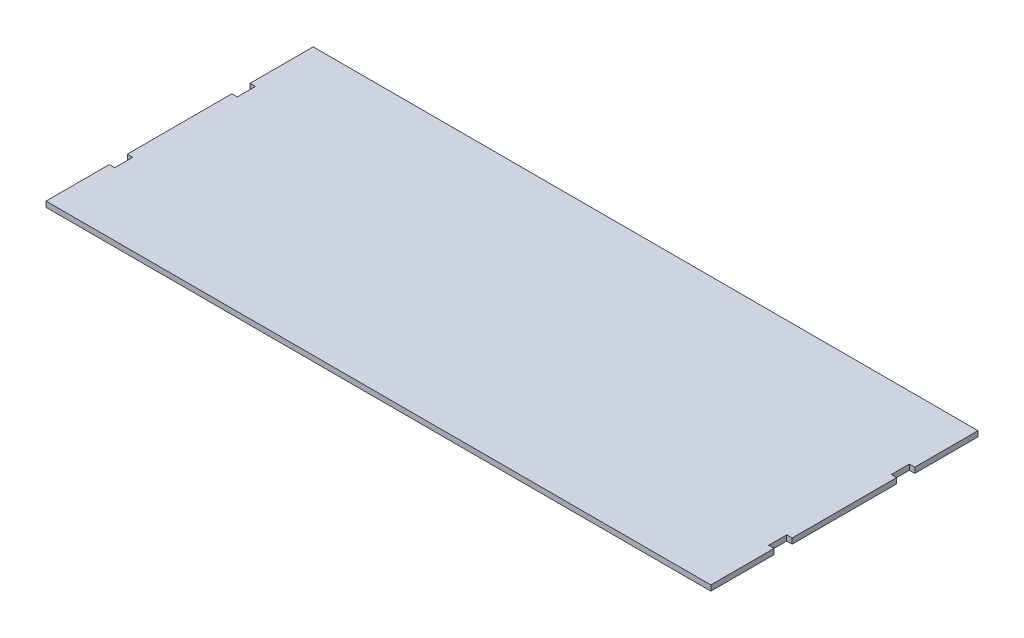
SolidWorks part; units mm, degrees
ref_plane "Front Plane" through (0, 0, 0) normal (0, 0, 1) x (1, 0, 0)
ref_plane "Top Plane" through (0, 0, 0) normal (0, 1, 0) x (1, 0, 0)
ref_plane "Right Plane" through (0, 0, 0) normal (1, 0, 0) x (0, 0, -1)
sketch "Sketch1" plane through (0, 0, 0) normal (0, 1, 0) x (1, 0, 0)
  line L5 (-184, 38.945) -> (-181, 38.945)
  line L6 (184, -73.945) -> (-184, -73.945)
  line L37 (184, -73.945) -> (184, -38.945)
  line L38 (184, 73.945) -> (-184, 73.945)
  line L39 (-184, -73.945) -> (-184, -38.945)
  line L40 (184, -73.945) -> (-184, 73.945) construction
  line L41 (184, 73.945) -> (-184, -73.945) construction
  line L42 (-181, 38.945) -> (-181, 28.945)
  line L43 (-181, 28.945) -> (-184, 28.945)
  line L46 (181, 28.945) -> (184, 28.945)
  line L47 (181, 38.945) -> (181, 28.945)
  line L48 (184, 38.945) -> (181, 38.945)
  line L49 (184, -38.945) -> (181, -38.945)
  line L50 (181, -38.945) -> (181, -28.945)
  line L51 (181, -28.945) -> (184, -28.945)
  line L52 (-181, -28.945) -> (-184, -28.945)
  line L53 (-181, -38.945) -> (-181, -28.945)
  line L54 (-184, -38.945) -> (-181, -38.945)
  line L55 (-184, 38.945) -> (-184, 73.945)
  line L56 (-184, -28.945) -> (-184, 28.945)
  line L57 (184, 38.945) -> (184, 73.945)
  line L58 (184, -28.945) -> (184, 28.945)
  point P0 (0, 0)
  dimension "D1" = 368
  dimension "D2" = 147.89
  dimension "D3" = 3
  dimension "D4" = 10
  dimension "D5" = 35
  dimension "D6" = 35
  dimension "D7" = 35
  dimension "D8" = 10
  dimension "D9" = 10
  dimension "D10" = 3
  dimension "D11" = 35
  dimension "D12" = 10
  dimension "D13" = 3
  dimension "D14" = 3
extrude "Boss-Extrude1" add sketch "Sketch1" along normal blind 3
